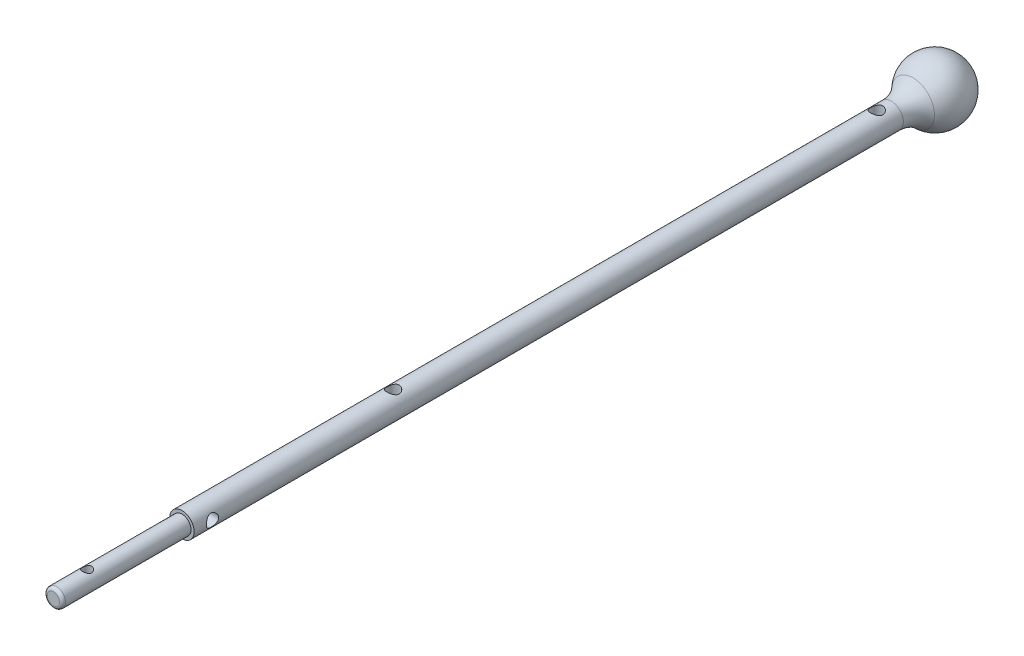
SolidWorks part; units mm, degrees
ref_plane "Front Plane" through (0, 0, 0) normal (0, 0, 1) x (1, 0, 0)
ref_plane "Top Plane" through (0, 0, 0) normal (0, 1, 0) x (1, 0, 0)
ref_plane "Right Plane" through (0, 0, 0) normal (1, 0, 0) x (0, 0, -1)
sketch "Sketch1" plane through (0, 0, 0) normal (0, 0, 1) x (1, 0, 0)
  circle A0 centre (0, 0) radius 1.5
  dimension "D1" = 3
extrude "Boss-Extrude1" add sketch "Sketch1" along normal blind 21
sketch "Sketch2" plane through (0, 0, 0) normal (0, 0, -1) x (-1, 0, 0)
  circle A2 centre (0, 0) radius 2
  circle A3 centre (0, 0) radius 2
  dimension "D1" = 0.5
extrude "Boss-Extrude2" add sketch "Sketch2" along normal blind 123
sketch "Sketch3" plane through (0, 0, 0) normal (0, 1, 0) x (1, 0, 0)
  line L0 (2, 123) -> (-2, 123) construction
  line L1 (-5, 123) -> (5, 123)
  arc A0 (5, 123) -> (-5, 123) centre (0, 123) ccw
  dimension "D1" = 10
revolve "Revolve1" add sketch "Sketch3" angle 360 about L1
fillet "Fillet1" radius 5 1 edges at (-2, 0, -118.4174)
fillet "Fillet2" radius 0.5 1 edges at (1.5, 0, 21)
sketch "Sketch4" plane through (0, 0, 0) normal (0, 1, 0) x (1, 0, 0)
  line L0 (-1, -21) -> (1, -21) construction
  line L1 (-1.5, 0) -> (1.5, 0) construction
  circle A0 centre (0, -15.5) radius 0.75
  circle A1 centre (0, 34.5) radius 1
  circle A2 centre (0, 113.5) radius 1
  dimension "D1" = 2
  dimension "D2" = 2
  dimension "D3" = 1.5
  dimension "D4" = 5.5
  dimension "D5" = 34.5
  dimension "D6" = 79
extrude "Cut-Extrude1" cut sketch "Sketch4" against normal through all both and the other way through all
sketch "Sketch5" plane through (0, 0, 0) normal (1, 0, 0) x (0, 0, -1)
  line L0 (-21, 1) -> (-21, -1) construction
  circle A0 centre (3, 0) radius 1
  dimension "D1" = 2
  dimension "D2" = 24
extrude "Cut-Extrude2" cut sketch "Sketch5" against normal through all both and the other way through all
